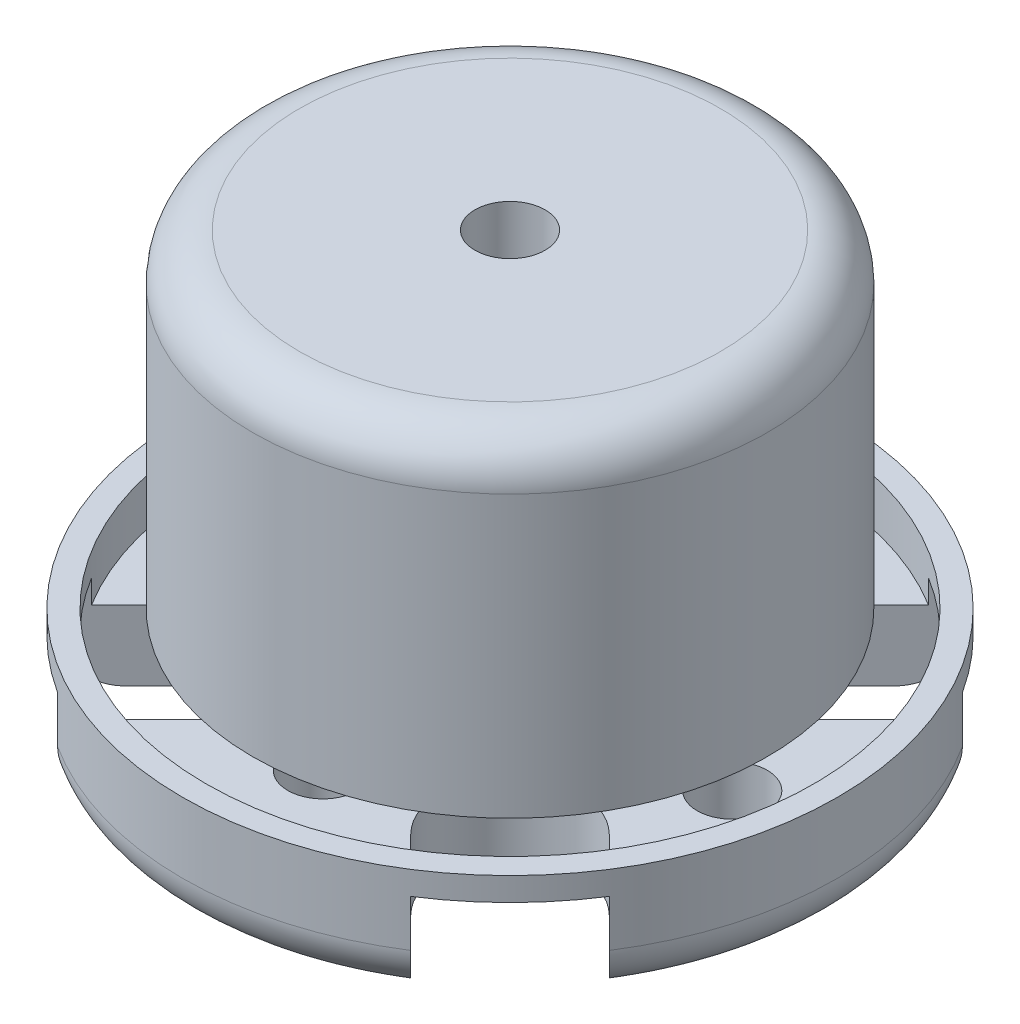
SolidWorks part; units mm, degrees
material "6061 合金"
ref_plane "前视基准面" through (0, 0, 0) normal (0, 0, 1) x (1, 0, 0)
ref_plane "上视基准面" through (0, 0, 0) normal (0, 1, 0) x (1, 0, 0)
ref_plane "右视基准面" through (0, 0, 0) normal (1, 0, 0) x (0, 0, -1)
sketch "草图1" plane through (0, 0, 0) normal (0, 1, 0) x (1, 0, 0)
  line L0 (-19.171, 0) -> (19.0369, 0) construction
  line L1 (0, 16.7875) -> (0, -18.6623) construction
  circle A0 centre (0, 0) radius 14
  circle A1 centre (0, 0) radius 9.5 construction
  circle A2 centre (0, 0) radius 8 construction
  circle A3 centre (-9.5, 0) radius 1.5
  circle A4 centre (9.5, 0) radius 1.5
  circle A5 centre (0, 8) radius 1.5
  circle A6 centre (0, -8) radius 1.5
  dimension "D1" = 28
  dimension "D2" = 19
  dimension "D3" = 16
  dimension "D4" = 3
extrude "凸台-拉伸1" add sketch "草图1" along normal blind 5
sketch "草图2" plane through (0, 5, 0) normal (0, 1, 0) x (1, 0, 0)
  circle A0 centre (0, 0) radius 4.5
  circle A1 centre (0, 0) radius 13
  dimension "D1" = 26
  dimension "D2" = 9
extrude "切除-拉伸1" cut sketch "草图2" against normal blind 2
sketch "草图3" plane through (0, 5, 0) normal (0, 1, 0) x (1, 0, 0)
  circle A0 centre (0, 0) radius 1.5
  dimension "D1" = 3
extrude "切除-拉伸2" cut sketch "草图3" against normal through all
sketch "草图4" plane through (0, 0, 0) normal (0, -1, 0) x (1, 0, 0)
  circle A0 centre (0, 0) radius 4
  dimension "D1" = 8
extrude "切除-拉伸3" cut sketch "草图4" against normal blind 3
sketch "草图5" plane through (0, 0, 0) normal (0, -1, 0) x (1, 0, 0)
  line L0 (0, 0) -> (9.8995, 9.8995) construction
  line L1 (8.4853, 4.2426) -> (11.7909, 7.5482)
  line L2 (4.2426, 8.4853) -> (7.5482, 11.7909)
  line L3 (8.4853, -4.2426) -> (11.7909, -7.5482)
  line L4 (4.2426, -8.4853) -> (7.5482, -11.7909)
  line L5 (-4.2426, -8.4853) -> (-7.5482, -11.7909)
  line L6 (-8.4853, -4.2426) -> (-11.7909, -7.5482)
  line L7 (-8.4853, 4.2426) -> (-11.7909, 7.5482)
  line L8 (-4.2426, 8.4853) -> (-7.5482, 11.7909)
  arc A0 (4.2426, 8.4853) -> (8.4853, 4.2426) centre (6.364, 6.364) ccw
  arc A1 (11.7909, 7.5482) -> (7.5482, 11.7909) centre (0, 0) ccw
  arc A2 (8.4853, -4.2426) -> (4.2426, -8.4853) centre (6.364, -6.364) ccw
  arc A3 (7.5482, -11.7909) -> (11.7909, -7.5482) centre (0, 0) ccw
  arc A4 (-4.2426, -8.4853) -> (-8.4853, -4.2426) centre (-6.364, -6.364) ccw
  arc A5 (-11.7909, -7.5482) -> (-7.5482, -11.7909) centre (0, 0) ccw
  arc A6 (-8.4853, 4.2426) -> (-4.2426, 8.4853) centre (-6.364, 6.364) ccw
  arc A7 (-7.5482, 11.7909) -> (-11.7909, 7.5482) centre (0, 0) ccw
  point P26 (0, 0)
  dimension "D1" = 6
  dimension "D2" = 9
  dimension "D3" = 4
extrude "切除-拉伸4" cut sketch "草图5" against normal blind 4
fillet "圆角1" radius 2 4 edges at (0, 0, -14) (14, 0, 0) (-14, 0, 0) (0, 0, 14)
sketch "草图6" plane through (0, 5, 0) normal (0, 1, 0) x (1, 0, 0)
  circle A0 centre (0, 0) radius 11
  circle A1 centre (0, 0) radius 1.5
  dimension "D1" = 22
extrude "凸台-拉伸3" add sketch "草图6" along normal blind 14
fillet "圆角2" radius 2 1 edges at (0, 19, 11)
sketch "草图7" plane through (0, 0, 0) normal (0, -1, 0) x (1, 0, 0)
  circle A0 centre (0, 0) radius 12 construction
sketch "草图8" plane through (0, 0, 0) normal (0, -1, 0) x (-1, 0, 0)
  line L0 (0, 8) -> (-9.5, 0) construction
  line L1 (-9.5, 0) -> (-18.5202, -7.596) construction
sketch "草图9" plane through (0, 0, 0) normal (0, -1, 0) x (1, 0, 0)
  line L0 (0, 0) -> (0, -12)
  line L2 (0, -8) -> (9.5, 0) construction
  line L3 (0, -12) -> (10.5531, -12) construction
  arc A3 (-6.0945, -10.3372) -> (6.0945, -10.3372) centre (0, 0) ccw construction
  point P4 (8.5079, -8.4626)
  point P7 (0, -12)
  point P11 (7.8673, -9.0612)
  point P12 (16.5401, -1.7596)
  point P15 (10.5481, -11.6755)
